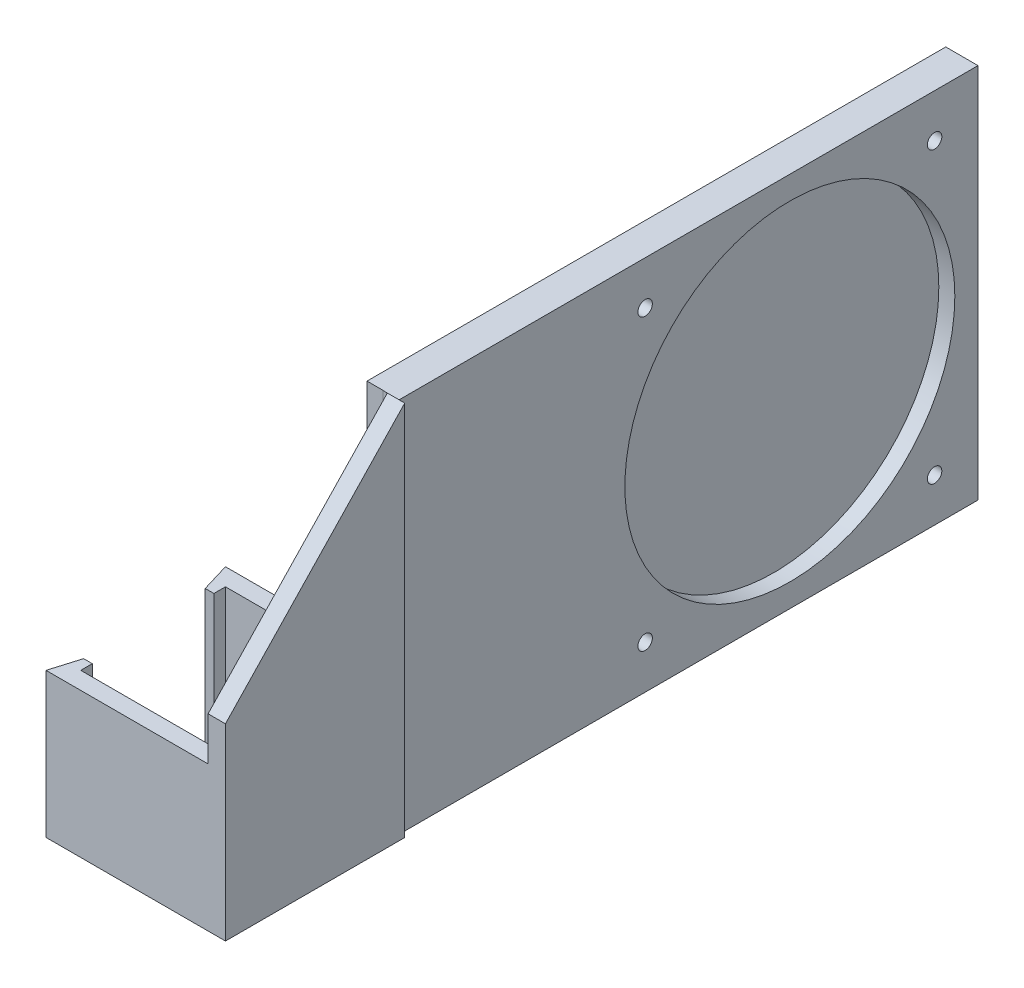
SolidWorks part; units mm, degrees
ref_plane "Спереди" through (0, 0, 0) normal (0, 0, 1) x (1, 0, 0)
ref_plane "Сверху" through (0, 0, 0) normal (0, 1, 0) x (1, 0, 0)
ref_plane "Справа" through (0, 0, 0) normal (1, 0, 0) x (0, 0, -1)
sketch "Эскиз1" plane through (0, 0, 0) normal (0, 1, 0) x (1, 0, 0)
  line L0 (-66.8258, 34.9697) -> (-66.8258, 29.9697)
  line L1 (-63.8258, 29.9697) -> (-63.8258, 31.9697)
  line L2 (-63.8258, 31.9697) -> (-38.8258, 31.9697)
  line L3 (-38.8258, 31.9697) -> (-38.8258, 6.9697)
  line L4 (-38.8258, 6.9697) -> (-63.8258, 6.9697)
  line L5 (-63.8258, 6.9697) -> (-63.8258, 8.9697)
  line L6 (-63.8258, 8.9697) -> (-66.8258, 8.9697)
  line L7 (-66.8258, 8.9697) -> (-66.8258, 3.9697)
  line L8 (-66.8258, 3.9697) -> (-22.1235, 3.9697)
  line L9 (-22.1235, 3.9697) -> (-36.579, 34.9697)
  line L10 (-36.579, 34.9697) -> (-66.8258, 34.9697)
  line L11 (-66.8258, 29.9697) -> (-63.8258, 29.9697)
  dimension "D1" = 25
  dimension "D2" = 25
  dimension "D3" = 25
  dimension "D4" = 155
  dimension "D5" = 3
  dimension "D6" = 3
  dimension "D7" = 3
  dimension "D8" = 3
  dimension "D9" = 2
  dimension "D10" = 2
extrude "Бобышка-Вытянуть1" add sketch "Эскиз1" along normal blind 25
sketch "Эскиз3" plane through (0, 0, 0) normal (0, -1, 0) x (1, 0, 0)
  line L0 (-66.8258, -3.9697) -> (-65.3258, -8.9697)
  line L1 (-63.8258, -8.9697) -> (-66.8258, -8.9697) construction
  line L2 (-65.3258, -8.9697) -> (-66.8258, -8.9697)
  line L3 (-66.8258, -8.9697) -> (-66.8258, -3.9697)
  line L4 (-66.8258, -29.9697) -> (-66.8258, -34.9697)
  line L5 (-66.8258, -34.9697) -> (-65.3258, -29.9697)
  line L6 (-66.8258, -29.9697) -> (-63.8258, -29.9697) construction
  line L7 (-65.3258, -29.9697) -> (-66.8258, -29.9697)
extrude "Вырез-Вытянуть4" cut sketch "Эскиз3" against normal through all
sketch "Эскиз7" plane through (0, 0, 0) normal (0, -1, 0) x (-1, 0, 0)
  line L1 (36.0076, 1.3029) -> (19.3993, 1.3029)
  line L2 (36.0076, 1.3029) -> (36.0076, 39.7765)
  line L3 (36.0076, 39.7765) -> (19.3993, 39.7765)
  line L4 (19.3993, 1.3029) -> (19.3993, 39.7765)
extrude "Вырез-Вытянуть14" cut sketch "Эскиз7" against normal through all
sketch "Эскиз8" plane through (0, 0, 0) normal (0, -1, 0) x (-1, 0, 0)
  line L0 (66.8258, 3.9697) -> (36.0076, 3.9697) construction
  line L1 (38.7989, 3.9697) -> (33.7989, 3.9697)
  line L2 (38.7989, 3.9697) -> (38.7989, 34.9383)
  line L3 (38.7989, 34.9383) -> (33.7989, 34.9383)
  line L4 (33.7989, 3.9697) -> (33.7989, 34.9383)
  dimension "D1" = 5
extrude "Бобышка-Вытянуть2" add sketch "Эскиз8" against normal up to surface (25 mm away) up to face at (-54.2963, 25, -20.5678)
sketch "Эскиз9" plane through (0, 0, -34.9383) normal (0, 0, -1) x (-1, 0, 0)
  line L0 (36.5643, 0) -> (33.7989, 0) construction
  line L1 (36.7989, 0) -> (39.5643, 0)
  line L2 (36.7989, 0) -> (36.7989, 65)
  line L3 (36.7989, 65) -> (39.5643, 65)
  line L4 (39.5643, 0) -> (39.5643, 65)
  line L6 (36.5643, 25) -> (36.5643, 0) construction
  dimension "D2" = 3
  dimension "D3" = 65
extrude "Бобышка-Вытянуть3" add sketch "Эскиз9" along normal blind 100
sketch "Эскиз10" plane through (0, 25, 0) normal (0, 1, 0) x (1, 0, 0)
  line L0 (-66.8258, 3.9697) -> (-33.7989, 3.9697) construction
  line L1 (-33.7989, 34.9383) -> (-38.8258, 34.9383)
  line L2 (-33.7989, 34.9383) -> (-33.7989, 3.9697)
  line L3 (-33.7989, 3.9697) -> (-38.8258, 3.9697)
  line L4 (-38.8258, 34.9383) -> (-38.8258, 3.9697)
extrude "Бобышка-Вытянуть4" add sketch "Эскиз10" along normal up to surface (40 mm away) up to face at (-38.1816, 65, -84.9383)
sketch "Эскиз11" plane through (-33.7989, 0, 0) normal (1, 0, 0) x (0, 0, -1)
  line L0 (34.9383, 65) -> (3.9697, 32.5) construction
  line L1 (3.9697, 65) -> (3.9697, 0) construction
  line L2 (34.9383, 65) -> (3.9697, 32.5)
  line L3 (3.9697, 32.5) -> (3.9697, 65)
  line L4 (3.9697, 65) -> (34.9383, 65)
extrude "Вырез-Вытянуть15" cut sketch "Эскиз11" against normal blind 100
sketch "Эскиз12" plane through (-36.7989, 0, 0) normal (1, 0, 0) x (0, 0, -1)
  line L0 (69.9383, 65) -> (69.9383, 0) construction
  line L1 (134.9383, 65) -> (34.9383, 65) construction
  line L2 (134.9383, 0) -> (34.9697, 0) construction
  line L3 (134.9383, 65) -> (134.9383, 0) construction
  line L4 (69.9383, 0) -> (134.9383, 65) construction
  circle A0 centre (102.4383, 32.5) radius 28.5
  dimension "D1" = 65
extrude "Вырез-Вытянуть16" cut sketch "Эскиз12" against normal blind 100
sketch "Эскиз13" plane through (-36.7989, 0, 0) normal (1, 0, 0) x (0, 0, -1)
  line L0 (134.9383, 32.5) -> (61.5486, 32.5) construction
  line L1 (134.9383, 65) -> (134.9383, 0) construction
  line L2 (102.4383, 32.5) -> (102.4383, 61) construction
  line L3 (102.4383, 61) -> (102.4383, 4) construction
  line L4 (65.365, 57.5) -> (138.8305, 57.5) construction
  line L5 (127.4383, 65) -> (127.4383, -8.7306) construction
  line L6 (134.9383, 65) -> (34.9383, 65) construction
  line L7 (62.5027, 7.5) -> (133.2422, 7.5) construction
  line L8 (77.4383, 65) -> (77.4383, 0) construction
  line L9 (134.9383, 0) -> (34.9697, 0) construction
  circle A0 centre (102.4383, 32.5) radius 28.5 construction
  circle A1 centre (77.4383, 57.5) radius 1.25
  circle A2 centre (127.4383, 57.5) radius 1.25
  circle A3 centre (127.4383, 7.5) radius 1.25
  circle A4 centre (77.4383, 7.5) radius 1.25
  dimension "D1" = 25
  dimension "D2" = 25
  dimension "D3" = 25
  dimension "D4" = 25
extrude "Вырез-Вытянуть17" cut sketch "Эскиз13" against normal blind 100
sketch "Эскиз14" plane through (0, 0, 0) normal (0, -1, 0) x (1, 0, 0)
  line L0 (-36.5643, -34.9383) -> (-33.7989, -34.9383) construction
  line L1 (-33.7989, -3.9697) -> (-35.8258, -3.9697)
  line L2 (-33.7989, -3.9697) -> (-33.7989, -34.9383)
  line L3 (-33.7989, -34.9383) -> (-35.8258, -34.9383)
  line L4 (-35.8258, -3.9697) -> (-35.8258, -34.9383)
  line L5 (-38.8258, -31.9697) -> (-38.8258, -6.9697) construction
  dimension "D1" = 3
extrude "Вырез-Вытянуть19" cut sketch "Эскиз14" against normal blind 100 contours L4 L3 L2 L1
sketch "Эскиз16" plane through (0, 0, 0) normal (0, -1, 0) x (1, 0, 0)
  line L1 (-39.5643, -34.9697) -> (-42.3725, -34.9697)
  line L2 (-39.5643, -34.9697) -> (-39.5643, -134.9443)
  line L3 (-39.5643, -134.9443) -> (-42.3725, -134.9443)
  line L4 (-42.3725, -34.9697) -> (-42.3725, -134.9443)
extrude "Бобышка-Вытянуть5" add sketch "Эскиз16" against normal up to surface (65 mm away) up to face at (-38.3105, 65, -74.9383)
sketch "Эскиз19" plane through (0, 0, 0) normal (0, -1, 0) x (1, 0, 0)
  line L0 (-38.8258, -31.9697) -> (-38.8258, -64.8007) construction
